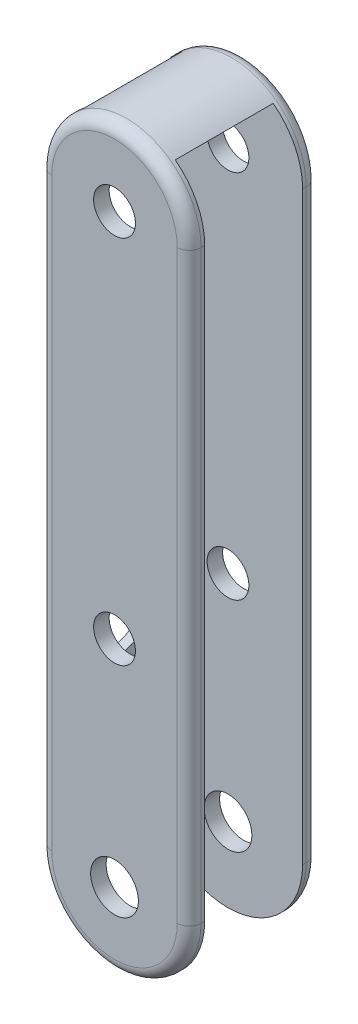
SolidWorks part; units mm, degrees
ref_plane "Face" through (0, 0, 0) normal (0, 0, 1) x (1, 0, 0)
ref_plane "Dessus" through (0, 0, 0) normal (0, 1, 0) x (1, 0, 0)
ref_plane "Droite" through (0, 0, 0) normal (1, 0, 0) x (0, 0, -1)
sketch "Esquisse1" plane through (0, 0, 0) normal (0, 0, 1) x (1, 0, 0)
  line L0 (0, 0) -> (0, 49)
  line L2 (12.5, 49) -> (12.5, 0)
  arc A0 (12.5, 0) -> (0, 0) centre (6.25, 0) cw
  arc A1 (12.5, 49) -> (0, 49) centre (6.25, 49) ccw
  dimension "D1" = 12.5
  dimension "D2" = 49
extrude "Base-Extrusion" add sketch "Esquisse1" along normal blind 10.8
fillet "Congé1" radius 1 4 edges at (6.25, 55.25, 10.8) (0, 24.5, 10.8) (6.25, -6.25, 10.8) (12.5, 24.5, 10.8)
fillet "Congé2" radius 1 4 edges at (0, 24.5, 0) (6.25, 55.25, 0) (12.5, 24.5, 0) (6.25, -6.25, 0)
sketch "Esquisse2" plane through (12.5, 0, 0) normal (1, 0, 0) x (0, 0, -1)
  line L0 (-1.3, -11.1264) -> (-1.3, 53.9745)
  line L1 (-1.3, 53.9745) -> (-9.5, 53.9745)
  line L2 (-9.5, 53.9745) -> (-9.5, -11.1264)
  line L3 (-9.5, -11.1264) -> (-1.3, -11.1264)
  line L4 (-10.8, 0) -> (-10.8, 49) construction
  line L5 (0, 49) -> (0, 0) construction
  dimension "D1" = 1.3
  dimension "D2" = 1.3
extrude "Enlèv. mat.-Extru.1" cut sketch "Esquisse2" against normal blind 11.7
sketch "Esquisse3" plane through (0, 0, 0) normal (-1, 0, 0) x (0, 0, 1)
  line L0 (1.4, 49.948) -> (1.4, 15.15)
  line L1 (10.8, 49) -> (10.8, 0) construction
  line L7 (9.4, 15.15) -> (9.4, 49.948)
  line L8 (9.5, -6.25) -> (9.5, 3.55)
  line L9 (9.5, 3.55) -> (1.3, 3.55)
  line L10 (1.3, 3.55) -> (1.3, -6.25)
  line L12 (1.3, -6.25) -> (9.5, -6.25)
  line L13 (9.4, 49.948) -> (1.4, 49.948)
  arc A0 (9.4, 15.15) -> (1.4, 15.15) centre (5.4, 15.15) cw
  dimension "D2" = 4
  dimension "D1" = 8.2
  dimension "D3" = 11.6
  dimension "D4" = 1.4
  dimension "D5" = 1.3
extrude "Enlèv. mat.-Extru.3" cut sketch "Esquisse3" against normal blind 11.7
sketch "Esquisse4" plane through (0, 0, 10.8) normal (0, 0, 1) x (1, 0, 0)
  circle A0 centre (6.25, 0) radius 2
  circle A1 centre (6.25, 49) radius 1.75
  arc A2 (11.5, 49) -> (1, 49) centre (6.25, 49) ccw construction
  arc A3 (1, 0) -> (11.5, 0) centre (6.25, 0) ccw construction
  circle A4 centre (6.25, 18) radius 1.75
  dimension "D1" = 18
  dimension "D2" = 4
  dimension "D3" = 3.5
extrude "Enlèv. mat.-Extru.4" cut sketch "Esquisse4" against normal through all
